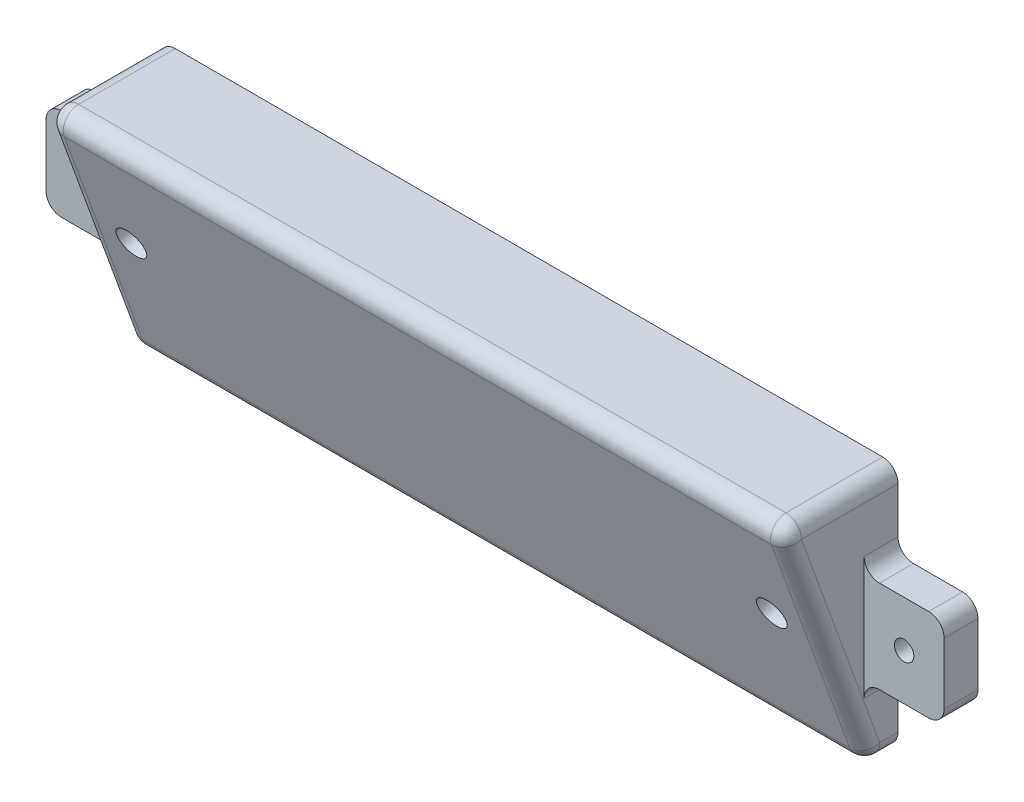
SolidWorks part; units mm, degrees
material "ABS"
ref_plane "X-Y Datum" through (0, 0, 0) normal (0, 0, 1) x (1, 0, 0)
ref_plane "X-Z Datum" through (0, 0, 0) normal (0, 1, 0) x (1, 0, 0)
ref_plane "Y-Z Datum" through (0, 0, 0) normal (1, 0, 0) x (0, 0, -1)
sketch "Sketch1" plane through (0, 0, 0) normal (0, 0, 1) x (1, 0, 0)
  line L0 (-76.2, 0) -> (76.2, 0) construction
  line L1 (-76.2, 25.4) -> (76.2, 25.4)
  line L2 (-76.2, 25.4) -> (-76.2, -25.4)
  line L3 (-76.2, -25.4) -> (76.2, -25.4)
  line L4 (76.2, 25.4) -> (76.2, -25.4)
  line L5 (-76.2, 25.4) -> (76.2, -25.4) construction
  line L6 (-76.2, -25.4) -> (76.2, 25.4) construction
  line L7 (-92.71, 9.525) -> (-76.2, -9.525) construction
  line L8 (-76.2, 9.525) -> (-92.71, 9.525)
  line L9 (-76.2, 9.525) -> (-76.2, -9.525)
  line L10 (-76.2, -9.525) -> (-92.71, -9.525)
  line L11 (-92.71, 9.525) -> (-92.71, -9.525)
  line L12 (0, -55) -> (0, 55) construction
  line L13 (76.2, 9.525) -> (92.71, 9.525)
  line L14 (92.71, 9.525) -> (92.71, -9.525)
  line L15 (76.2, -9.525) -> (92.71, -9.525)
  line L16 (92.71, 9.525) -> (76.2, -9.525) construction
  circle A0 centre (-84.455, 0) radius 2
  circle A1 centre (84.455, 0) radius 2
  point P0 (0, 0)
  point P12 (-92.71, 0)
  dimension "D3" = 4
  dimension "D1" = 152.4
  dimension "D2" = 50.8
  dimension "D4" = 19.05
  dimension "D5" = 16.51
extrude "Boss-Extrude1" add sketch "Sketch1" along normal blind 6 contours L4 L1 L2 L3
sketch "Sketch5" plane through (-76.2, 0, 0) normal (-1, 0, 0) x (0, 0, 1)
  line L0 (6, 25.4) -> (24.4897, 25.4)
  line L1 (24.4897, 25.4) -> (6, -25.4)
  line L2 (6, 25.4) -> (6, -25.4) construction
  line L3 (6, 25.4) -> (6, -25.4)
  dimension "D1" = 20
extrude "Boss-Extrude2" add sketch "Sketch5" against normal up to surface (152.4 mm away) up to face at (76.2, 0, 3)
sketch "Sketch7" plane through (0, 0, 0) normal (0, 0, -1) x (-1, 0, 0)
  line L0 (-76.2, 9.525) -> (-92.71, 9.525) construction
  line L1 (-92.71, 9.525) -> (-92.71, -9.525) construction
  line L2 (-76.2, -9.525) -> (-92.71, -9.525) construction
  line L3 (-76.2, 9.525) -> (-92.71, 9.525)
  line L4 (92.71, 9.525) -> (76.2, 9.525)
  line L5 (92.71, -9.525) -> (92.71, 9.525)
  line L6 (76.2, -9.525) -> (92.71, -9.525)
  line L7 (76.2, 9.525) -> (76.2, -9.525)
  line L8 (92.71, 9.525) -> (76.2, 9.525)
  line L9 (92.71, -9.525) -> (92.71, 9.525)
  line L10 (76.2, -9.525) -> (92.71, -9.525)
  line L11 (76.2, 9.525) -> (76.2, -9.525)
  line L12 (76.2, 25.4) -> (-76.2, 25.4)
  line L13 (-76.2, 25.4) -> (-76.2, -25.4)
  line L14 (-76.2, -25.4) -> (76.2, -25.4)
  line L15 (76.2, -25.4) -> (76.2, 25.4)
  line L16 (76.2, 25.4) -> (-76.2, 25.4)
  line L17 (-76.2, 25.4) -> (-76.2, -25.4)
  line L18 (-76.2, -25.4) -> (76.2, -25.4)
  line L19 (76.2, -25.4) -> (76.2, 25.4)
  line L20 (-92.71, 9.525) -> (-92.71, -9.525)
  line L21 (-76.2, -9.525) -> (-92.71, -9.525)
  circle A1 centre (84.455, 0) radius 2
  circle A2 centre (84.455, 0) radius 2
  circle A3 centre (-84.455, 0) radius 2
  circle A4 centre (-84.455, 0) radius 2
  line M14 (-76.2, 25.4) -> (-76.2, -25.4)
  line M16 (76.2, -25.4) -> (76.2, 25.4)
  dimension "D1" = 0
  dimension "D2" = 0
  dimension "D3" = 0
  dimension "D4" = 0
extrude "Boss-Extrude3" add sketch "Sketch7" against normal blind 7 contours L21 L3 L20 A4 M14 | L10 L9 L8 A2 M16
fillet "Fillet1" radius 3.175 16 edges at (76.2, 9.525, 3.5) (92.71, 9.525, 3.5) (92.71, -9.525, 3.5) (76.2, -9.525, 3.5) (-76.2, -9.525, 3.5) (-76.2, 9.525, 3.5) (-92.71, 9.525, 3.5) (-92.71, -9.525, 3.5) (76.2, 0, 15.2448) (76.2, -25.4, 3) (76.2, 25.4, 12.2448) (0, 25.4, 24.4897) (-76.2, 0, 15.2448) (0, -25.4, 6) (-76.2, -25.4, 3) (-76.2, 25.4, 12.2448)
sketch "Sketch8" plane through (0, -4.8996, 13.4615) normal (0, -0.342, 0.9397) x (1, 0, 0)
  circle A0 centre (-66.1187, 7.3558) radius 3.025
  circle A1 centre (66.1188, 7.3558) radius 3.025
  point P0 (66.1188, 7.3558)
  point P1 (-66.1187, 7.3558)
  dimension "D1" = 6.05
extrude "Cut-Extrude1" cut sketch "Sketch8" against normal blind 10
